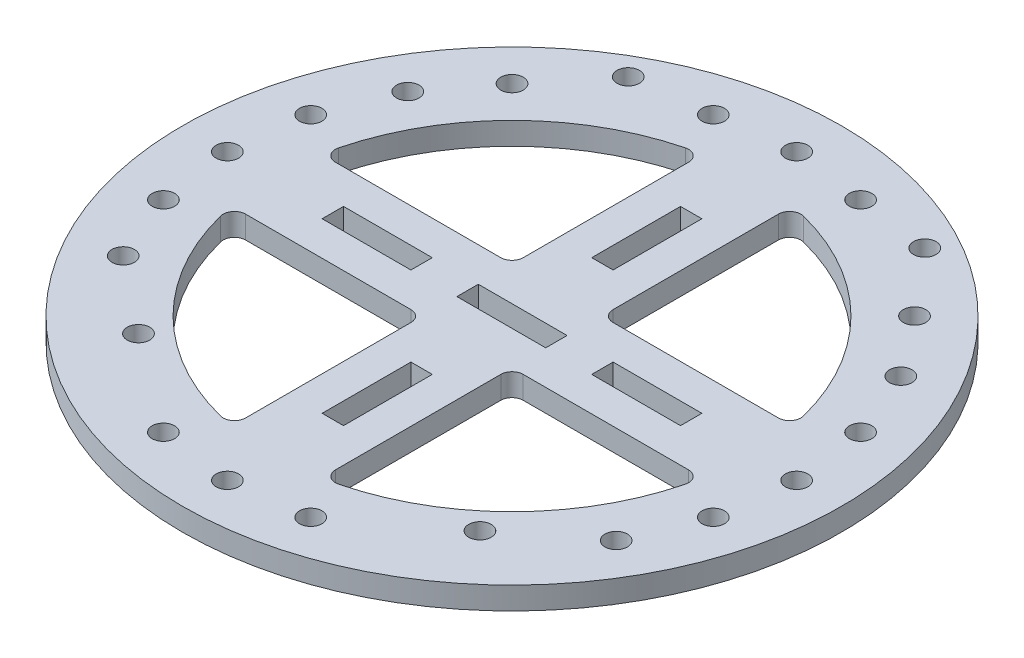
SolidWorks part; units mm, degrees
material "Acrylic (Medium-high impact)"
ref_plane "Front Plane" through (0, 0, 0) normal (0, 0, 1) x (1, 0, 0)
ref_plane "Top Plane" through (0, 0, 0) normal (0, 1, 0) x (1, 0, 0)
ref_plane "Right Plane" through (0, 0, 0) normal (1, 0, 0) x (0, 0, -1)
sketch "Sketch1" plane through (0, 0, 0) normal (0, 1, 0) x (1, 0, 0)
  line L0 (-6.35, -39.9994) -> (-6.35, -16.6393)
  line L1 (-1.5113, 16.622) -> (1.5113, 16.622)
  line L2 (6.35, -39.9994) -> (6.35, -16.6393)
  line L3 (1.5113, 4.0744) -> (1.5113, 16.622)
  line L4 (-31.2976, -2.3518) -> (-7.9375, -2.3518)
  line L5 (-1.5113, 4.0744) -> (1.5113, 4.0744)
  line L6 (-1.5113, 4.0744) -> (-1.5113, 16.622)
  line L7 (-25.3238, -7.1905) -> (-12.7762, -7.1905)
  line L8 (-31.2976, -15.0518) -> (-7.9375, -15.0518)
  line L12 (-12.7762, -10.2131) -> (-12.7762, -7.1905)
  line L13 (-25.3238, -10.2131) -> (-12.7762, -10.2131)
  line L16 (-25.3238, -10.2131) -> (-25.3238, -7.1905)
  line L19 (-6.2738, -7.1905) -> (6.2738, -7.1905)
  line L20 (6.2738, -10.2131) -> (6.2738, -7.1905)
  line L22 (-6.2738, -10.2131) -> (6.2738, -10.2131)
  line L24 (-6.2738, -10.2131) -> (-6.2738, -7.1905)
  line L25 (12.7762, -7.1905) -> (25.3238, -7.1905)
  line L26 (25.3238, -10.2131) -> (25.3238, -7.1905)
  line L27 (12.7762, -10.2131) -> (25.3238, -10.2131)
  line L29 (12.7762, -10.2131) -> (12.7762, -7.1905)
  line L30 (-1.5113, -21.478) -> (1.5113, -21.478)
  line L31 (1.5113, -34.0256) -> (1.5113, -21.478)
  line L32 (-1.5113, -34.0256) -> (1.5113, -34.0256)
  line L33 (-1.5113, -34.0256) -> (-1.5113, -21.478)
  line L49 (7.9375, -15.0518) -> (31.2976, -15.0518)
  line L51 (6.35, -0.7643) -> (6.35, 22.5957)
  line L52 (7.9375, -2.3518) -> (31.2976, -2.3518)
  line L54 (-6.35, -0.7643) -> (-6.35, 22.5957)
  circle A0 centre (0, -8.7018) radius 46.5759
  arc A1 (-32.8363, -17.0296) -> (-8.3278, -41.5382) centre (0, -8.7018) ccw
  arc A2 (8.3278, -41.5382) -> (32.8363, -17.0296) centre (0, -8.7018) ccw
  circle A3 centre (0, 31.5241) radius 1.5875
  circle A4 centre (-21.0623, 28.7859) radius 1.5875
  circle A5 centre (20.8477, 28.7859) radius 1.5875
  circle A6 centre (24.0227, -37.2541) radius 1.5875
  circle A7 centre (-24.2373, -37.2541) radius 1.5875
  circle A8 centre (10.4112, 30.1534) radius 1.5875
  arc A9 (32.8363, -0.3741) -> (8.3278, 24.1345) centre (0, -8.7018) ccw
  arc A10 (-8.3278, 24.1345) -> (-32.8363, -0.3741) centre (0, -8.7018) ccw
  circle A12 centre (28.444, 19.7422) radius 1.5875
  circle A13 centre (34.8367, 11.4111) radius 1.5875
  circle A14 centre (38.8552, 1.7094) radius 1.5875
  circle A15 centre (40.2259, -8.7018) radius 1.5875
  arc A16 (31.2976, -15.0518) -> (32.8363, -17.0296) centre (31.2976, -16.6393) cw
  arc A17 (6.35, -39.9994) -> (8.3278, -41.5382) centre (7.9375, -39.9994) ccw
  circle A18 centre (38.8552, -19.1131) radius 1.5875
  circle A19 centre (34.8367, -28.8148) radius 1.5875
  arc A21 (7.9375, -15.0518) -> (6.35, -16.6393) centre (7.9375, -16.6393) ccw
  arc A22 (31.2976, -2.3518) -> (32.8363, -0.3741) centre (31.2976, -0.7643) ccw
  circle A24 centre (10.4112, -47.5571) radius 1.5875
  circle A25 centre (0, -48.9277) radius 1.5875
  circle A26 centre (-10.4112, -47.5571) radius 1.5875
  arc A28 (6.35, -0.7643) -> (7.9375, -2.3518) centre (7.9375, -0.7643) ccw
  arc A29 (6.35, 22.5957) -> (8.3278, 24.1345) centre (7.9375, 22.5957) cw
  arc A31 (-6.35, 22.5957) -> (-8.3278, 24.1345) centre (-7.9375, 22.5957) ccw
  circle A32 centre (-34.8367, -28.8148) radius 1.5875
  circle A33 centre (-38.8552, -19.1131) radius 1.5875
  circle A34 centre (-40.2259, -8.7018) radius 1.5875
  circle A35 centre (-38.8552, 1.7094) radius 1.5875
  circle A36 centre (-34.8367, 11.4111) radius 1.5875
  circle A37 centre (-28.444, 19.7422) radius 1.5875
  circle A39 centre (-10.4112, 30.1534) radius 1.5875
  arc A40 (-7.9375, -2.3518) -> (-6.35, -0.7643) centre (-7.9375, -0.7643) ccw
  arc A41 (-31.2976, -2.3518) -> (-32.8363, -0.3741) centre (-31.2976, -0.7643) cw
  arc A42 (-6.35, -16.6393) -> (-7.9375, -15.0518) centre (-7.9375, -16.6393) ccw
  arc A43 (-6.35, -39.9994) -> (-8.3278, -41.5382) centre (-7.9375, -39.9994) cw
  arc A44 (-31.2976, -15.0518) -> (-32.8363, -17.0296) centre (-31.2976, -16.6393) ccw
  circle A59 centre (-20.113, 26.1348) radius 1.5875 [skipped]
  circle A60 centre (20.113, 26.1348) radius 1.5875 [skipped]
  circle A61 centre (28.444, -37.1458) radius 1.5875 [skipped]
  circle A62 centre (20.113, -43.5385) radius 1.5875 [skipped]
  circle A63 centre (-20.113, -43.5385) radius 1.5875 [skipped]
  circle A64 centre (-28.444, -37.1458) radius 1.5875 [skipped]
  point P6 (33.2754, -15.0518)
  point P13 (6.35, -41.9773)
  point P29 (33.2754, -2.3518)
  point P41 (6.35, -2.3518)
  point P46 (6.35, 24.5736)
  point P57 (-6.35, 24.5736)
  point P66 (-6.35, -2.3518)
  point P106 (0, -8.7018)
  dimension "D1" = 24
extrude "Boss-Extrude1" add sketch "Sketch1" along normal blind 3.175
